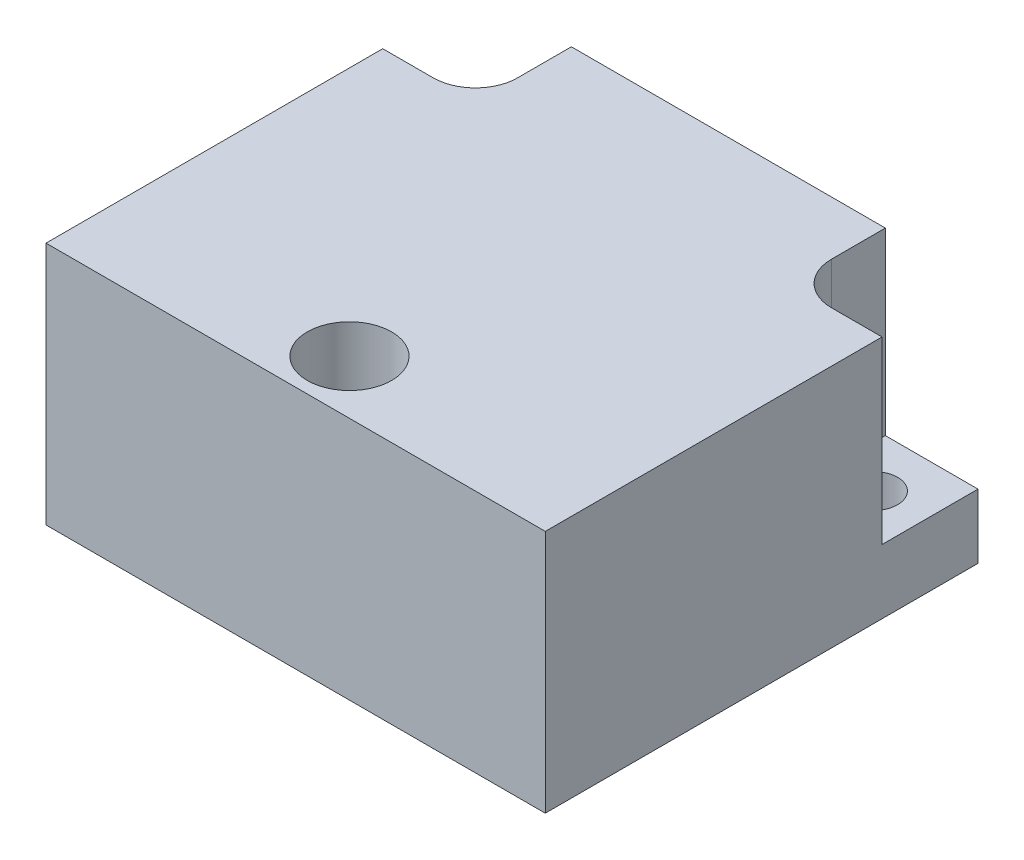
SolidWorks part; units mm, degrees
ref_plane "Front Plane" through (0, 0, 0) normal (0, 0, 1) x (1, 0, 0)
ref_plane "Top Plane" through (0, 0, 0) normal (0, 1, 0) x (1, 0, 0)
ref_plane "Right Plane" through (0, 0, 0) normal (1, 0, 0) x (0, 0, -1)
sketch "Sketch1" plane through (0, 0, 0) normal (0, 1, 0) x (1, 0, 0)
  line L1 (-22.5, -19.5) -> (22.5, -19.5)
  line L2 (-22.5, -19.5) -> (-22.5, 19.5)
  line L3 (-22.5, 19.5) -> (22.5, 19.5)
  line L4 (22.5, -19.5) -> (22.5, 19.5)
  line L5 (-22.5, -19.5) -> (22.5, 19.5) construction
  line L6 (-22.5, 19.5) -> (22.5, -19.5) construction
  point P0 (0, 0)
  dimension "D1" = 39
  dimension "D2" = 45
extrude "Boss-Extrude1" add sketch "Sketch1" along normal blind 22
sketch "Sketch2" plane through (0, 0, 0) normal (0, -1, 0) x (1, 0, 0)
  line L0 (-22.5, -19.5) -> (-22.5, 19.5) construction
  line L1 (22.5, 19.5) -> (22.5, -19.5) construction
  line L2 (22.5, -19.5) -> (-22.5, -19.5) construction
  line L3 (-22.5, 19.5) -> (22.5, 19.5) construction
  point P0 (0, 14.65)
  point P1 (-17.95, -14.65)
  point P2 (17.95, -14.65)
  dimension "D1" = 4.55
  dimension "D2" = 4.55
  dimension "D3" = 4.85
  dimension "D4" = 4.85
  dimension "D5" = 4.85
  dimension "D6" = 22.5
hole_wizard "M4 Clearance Hole1" positions "Sketch4" profile "Sketch3" hole size "M4" standard "ANSI Metric" end condition through all
sketch "Sketch4" plane through (0, 0, 0) normal (0, -1, 0) x (-1, 0, 0)
  point P0 (0, -14.65)
  point P3 (-17.95, 14.65)
  point P6 (17.95, 14.65)
sketch "Sketch3" plane through (0, 0, 14.65) normal (1, 0, 0) x (0, 0, -1)
  line L0 (0, 0) -> (0, 22)
  line L1 (0, 22) -> (2.15, 22)
  line L2 (2.15, 22) -> (2.15, 0)
  line L5 (2.15, 0) -> (0, 0)
  line L11 (0, -6.35) -> (0, 107.95) construction
  dimension "Thru Hole Dia." = 4.3
  dimension "Thru Hole Depth" = 22
sketch "Sketch5" plane through (0, 22, 0) normal (0, 1, 0) x (1, 0, 0)
  line L0 (-14.15, 14.65) -> (-14.15, 22.25)
  line L1 (-14.15, 22.25) -> (-25.55, 22.25)
  line L2 (-25.55, 22.25) -> (-25.55, 10.85)
  line L3 (-25.55, 10.85) -> (-17.95, 10.85)
  line L4 (17.95, 10.85) -> (25.55, 10.85)
  line L5 (25.55, 10.85) -> (25.55, 22.25)
  line L6 (25.55, 22.25) -> (14.15, 22.25)
  line L7 (14.15, 22.25) -> (14.15, 14.65)
  arc A0 (-17.95, 10.85) -> (-14.15, 14.65) centre (-17.95, 14.65) ccw
  arc A1 (14.15, 14.65) -> (17.95, 10.85) centre (17.95, 14.65) ccw
  circle A2 centre (0, -14.65) radius 3.8
  dimension "D1" = 7.6
  dimension "D2" = 7.6
  dimension "D3" = 7.6
  dimension "D4" = 7.6
  dimension "D5" = 7.6
  dimension "D6" = 7.6
  dimension "D7" = 11.4
  dimension "D8" = 7.6
extrude "Cut-Extrude1" cut sketch "Sketch5" against normal blind 16.2
